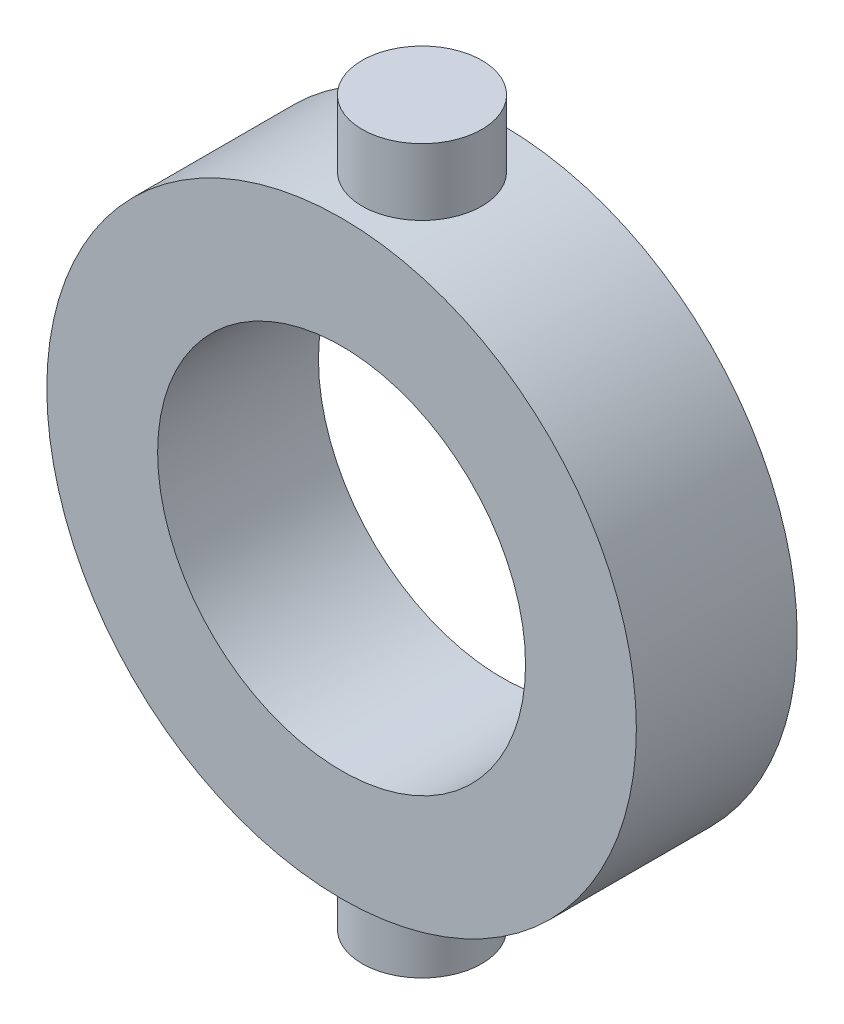
SolidWorks part; units mm, degrees
ref_plane "Front Plane" through (0, 0, 0) normal (0, 0, 1) x (1, 0, 0)
ref_plane "Top Plane" through (0, 0, 0) normal (0, 1, 0) x (1, 0, 0)
ref_plane "Right Plane" through (0, 0, 0) normal (1, 0, 0) x (0, 0, -1)
sketch "Sketch1" plane through (0, 0, 0) normal (0, 1, 0) x (1, 0, 0)
  line L0 (0, 0) -> (0, 104.6198) construction
  line L6 (-66.5, -18.1407) -> (-41.5, -18.1407)
  line L7 (-66.5, -18.1407) -> (-66.5, 18.1407)
  line L8 (-66.5, 18.1407) -> (-41.5, 18.1407)
  line L9 (-41.5, -18.1407) -> (-41.5, 18.1407)
  line L10 (-66.5, -18.1407) -> (-41.5, 18.1407) construction
  line L11 (-66.5, 18.1407) -> (-41.5, -18.1407) construction
  point P2 (-54, 0)
  dimension "D1" = 41.5
  dimension "D2" = 25
revolve "Revolve1" add sketch "Sketch1" angle 360 about L0
ref_plane "Plane1" through (0, 66.5, 0) normal (0, 1, 0) x (1, 0, 0)
sketch "Sketch3" plane through (0, 66.5, 0) normal (0, 1, 0) x (1, 0, 0)
  circle A0 centre (0, 0) radius 13.5
  dimension "D1" = 27
extrude "Boss-Extrude1" add sketch "Sketch3" along normal blind 15 separate body contours A0
ref_plane "Plane2" through (0, -66.5, 0) normal (0, 1, 0) x (1, 0, 0)
sketch "Sketch4" plane through (0, -66.5, 0) normal (0, 1, 0) x (1, 0, 0)
  circle A0 centre (0, 0) radius 13.5
extrude "Boss-Extrude3" add sketch "Sketch4" against normal blind 15 separate body
